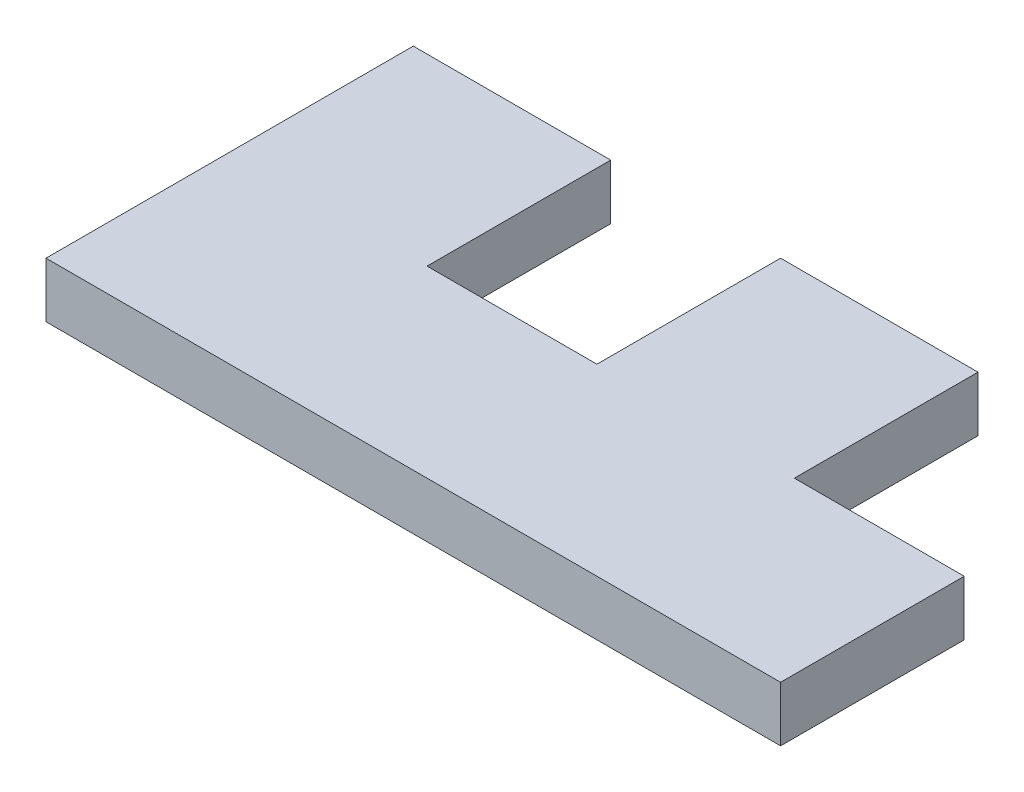
SolidWorks part; units mm, degrees
ref_plane "Front Plane" through (0, 0, 0) normal (0, 0, 1) x (1, 0, 0)
ref_plane "Top Plane" through (0, 0, 0) normal (0, 1, 0) x (1, 0, 0)
ref_plane "Right Plane" through (0, 0, 0) normal (1, 0, 0) x (0, 0, -1)
sketch "Sketch1" plane through (0, 0, 0) normal (0, 1, 0) x (1, 0, 0)
  line L1 (0, 0) -> (40, 0)
  line L2 (0, 0) -> (0, 20)
  line L3 (0, 20) -> (40, 20)
  line L4 (40, 0) -> (40, 20)
  dimension "D1" = 20
  dimension "D2" = 40
extrude "Boss-Extrude1" add sketch "Sketch1" along normal blind 3
sketch "Sketch2" plane through (0, 3, 0) normal (0, 1, 0) x (1, 0, 0)
  line L0 (10.75, 20) -> (10.75, 10)
  line L1 (40, 20) -> (0, 20) construction
  line L2 (10.75, 10) -> (20, 10)
  line L3 (20, 10) -> (20, 20)
  line L4 (20, 20) -> (10.75, 20)
  line L5 (30.75, 20) -> (30.75, 10)
  line L6 (30.75, 10) -> (40, 10)
  line L7 (40, 10) -> (40, 20)
  line L8 (40, 20) -> (30.75, 20)
  line L19 (0, 20) -> (0, 0) construction
  dimension "D1" = 9.25
  dimension "D2" = 10.75
  dimension "D3" = 10
  dimension "D4" = 10.75
  dimension "D5" = 9.25
extrude "Cut-Extrude1" cut sketch "Sketch2" against normal blind 3
equation "\"Mat_thick\"=3"
equation "\"inset\"=0.75"
equation "\"outset\"=0.75"
equation "\"D2@Sketch2\"=10.00mm+\"outset\""
equation "\"D1@Sketch2\"=10-\"inset\""
equation "\"D4@Sketch2\"=10+\"outset\""
equation "\"D5@Sketch2\"=10.00-\"inset\""
